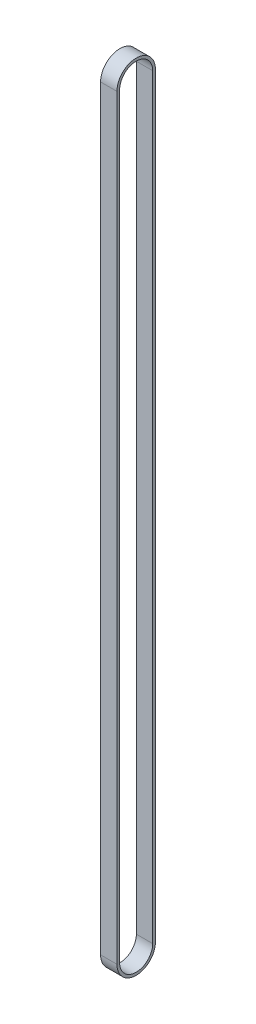
SolidWorks part; units mm, degrees
material "6063-T5"
ref_plane "Front Plane" through (0, 0, 0) normal (1, 0, 0) x (0, 1, 0)
ref_plane "Top Plane" through (0, 0, 0) normal (0, 0, 1) x (0, 1, 0)
ref_plane "Right Plane" through (0, 0, 0) normal (0, 1, 0) x (-1, 0, 0)
sketch "Sketch1" plane through (0, 0, 0) normal (1, 0, 0) x (0, 1, 0)
  line L0 (-140, 0) -> (140, 0) construction
  line L1 (-140, 6.125) -> (140, 6.125)
  line L2 (-140, -6.125) -> (140, -6.125)
  line L3 (-140, 7.125) -> (140, 7.125)
  line L4 (-140, -7.125) -> (140, -7.125)
  arc A0 (-140, 6.125) -> (-140, -6.125) centre (-140, 0) ccw
  arc A1 (140, -6.125) -> (140, 6.125) centre (140, 0) ccw
  arc A2 (140, -7.125) -> (140, 7.125) centre (140, 0) ccw
  arc A3 (-140, 7.125) -> (-140, -7.125) centre (-140, 0) ccw
  point P2 (0, 0)
  dimension "D2" = 6.125
  dimension "D1" = 280
  dimension "D3" = 1
extrude "Boss-Extrude1" add sketch "Sketch1" along normal blind 6.05
